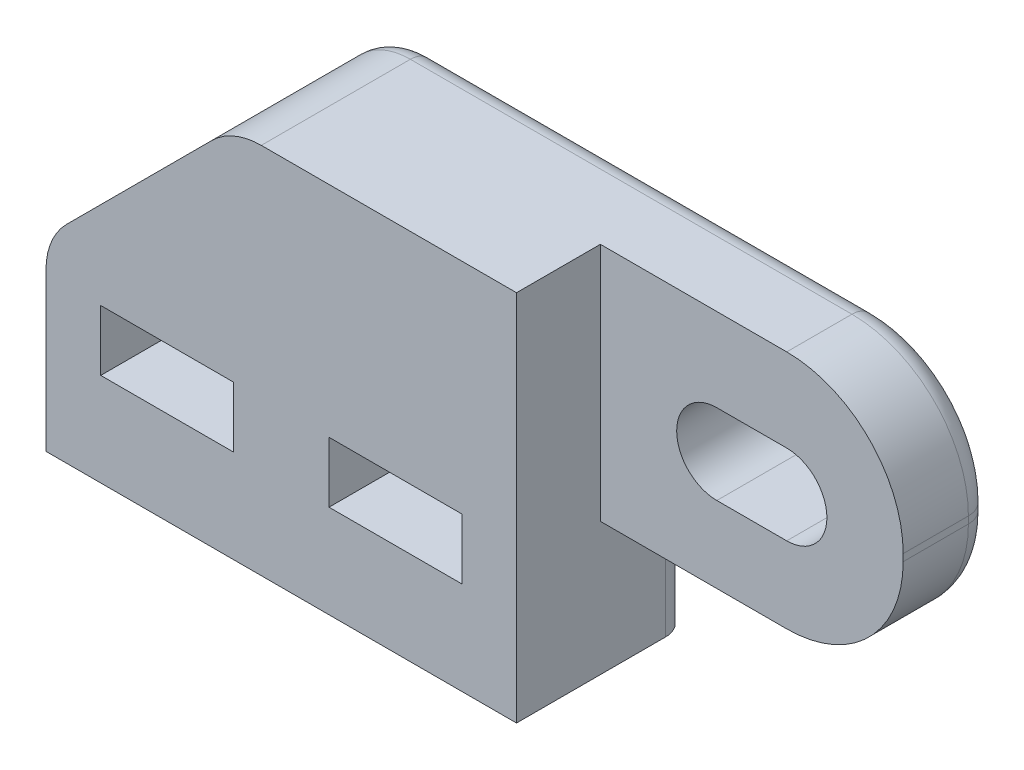
SolidWorks part; units mm, degrees
material "ABS"
ref_plane "Front Plane" through (0, 0, 0) normal (0, 0, 1) x (1, 0, 0)
ref_plane "Top Plane" through (0, 0, 0) normal (0, 1, 0) x (1, 0, 0)
ref_plane "Right Plane" through (0, 0, 0) normal (1, 0, 0) x (0, 0, -1)
sketch "Sketch1" plane through (0, 0, 0) normal (0, 0, 1) x (1, 0, 0)
  line L0 (0, 0) -> (20.2, 0)
  line L1 (20.2, 0) -> (20.2, 5.7)
  line L2 (20.2, 5.7) -> (33.2, 5.7)
  line L3 (33.2, 5.7) -> (33.2, 16)
  line L4 (33.2, 16) -> (0, 16)
  line L5 (0, 16) -> (0, 0)
  line L6 (25.2, 16) -> (25.2, 5.7) construction
  line L7 (25.2, 12.425) -> (28.2, 12.425)
  line L8 (25.2, 8.975) -> (28.2, 8.975)
  arc A0 (25.2, 12.425) -> (25.2, 8.975) centre (25.2, 10.7) ccw
  arc A1 (28.2, 8.975) -> (28.2, 12.425) centre (28.2, 10.7) ccw
  dimension "D6" = 3.45
  dimension "D1" = 20.2
  dimension "D2" = 5.7
  dimension "D3" = 5
  dimension "D4" = 5
  dimension "D5" = 16
  dimension "D7" = 8
  dimension "D8" = 3
extrude "Boss-Extrude1" add sketch "Sketch1" along normal blind 7.4
sketch "Sketch2" plane through (33.2, 0, 0) normal (1, 0, 0) x (0, 0, -1)
  line L1 (-3.8, 5.7) -> (-7.4, 5.7)
  line L2 (-3.8, 5.7) -> (-3.8, 16)
  line L3 (-3.8, 16) -> (-7.4, 16)
  line L4 (-7.4, 5.7) -> (-7.4, 16)
  line L5 (-7.4, 16) -> (0, 16) construction
  dimension "D1" = 3.6
extrude "Cut-Extrude1" cut sketch "Sketch2" against normal up to surface (13 mm away) up to face at (20.2, 2.85, 3.7)
sketch "Sketch4" plane through (0, 0, 0) normal (0, -1, 0) x (1, 0, 0)
  line L0 (10.1, 0) -> (10.1, 7.4) construction
  line L3 (20.2, 2.75) -> (0, 2.75) construction
  line L5 (0, 7.4) -> (20.2, 7.4) construction
  line L7 (0, 0) -> (20.2, 0) construction
  line L8 (0, 7.4) -> (0, 0) construction
  line L9 (20.2, 7.4) -> (20.2, 0) construction
  circle A0 centre (15, 2.75) radius 1.725
  circle A1 centre (5.2, 2.75) radius 1.725
  dimension "D1" = 3.45
  dimension "D2" = 9.8
  dimension "D3" = 10.1
  dimension "D4" = 2.75
extrude "Cut-Extrude3" cut sketch "Sketch4" against normal blind 9
sketch "Sketch3" plane through (0, 0, 0) normal (0, 0, -1) x (-1, 0, 0)
  line L0 (-15, 9) -> (-15, 0) construction
  line L1 (-17.85, 6.6) -> (-12.15, 6.6)
  line L2 (-17.85, 6.6) -> (-17.85, 4)
  line L3 (-17.85, 4) -> (-12.15, 4)
  line L4 (-12.15, 6.6) -> (-12.15, 4)
  line L5 (-17.85, 6.6) -> (-12.15, 4) construction
  line L6 (-17.85, 4) -> (-12.15, 6.6) construction
  line L7 (-8.05, 6.6) -> (-2.35, 6.6)
  line L8 (-8.05, 6.6) -> (-8.05, 4)
  line L9 (-8.05, 4) -> (-2.35, 4)
  line L10 (-2.35, 6.6) -> (-2.35, 4)
  line L11 (-8.05, 6.6) -> (-2.35, 4) construction
  line L12 (-8.05, 4) -> (-2.35, 6.6) construction
  line L13 (-5.2, 9) -> (-5.2, 0) construction
  point P0 (-15, 5.3)
  point P5 (-5.2, 5.3)
  dimension "D1" = 9.8
  dimension "D2" = 4
  dimension "D3" = 2.6
  dimension "D4" = 5.7
extrude "Cut-Extrude4" cut sketch "Sketch3" against normal through all
chamfer "Chamfer1" distance 8 angle 45 1 edges at (0, 16, 3.7)
fillet "Fillet4" radius 3 2 edges at (8, 16, 3.7) (0, 8, 3.7)
fillet "Fillet5" radius 5 2 edges at (33.2, 5.7, 1.9) (33.2, 16, 1.9)
fillet "Fillet6" radius 1 10 edges at (24.2, 5.7, 0) (31.7355, 7.1645, 0) (33.2, 10.85, 0) (31.7355, 14.5355, 0) (18.7213, 16, 0) (8.0946, 15.7716, 0) (4, 12, 0) (0.2284, 7.9054, 0) (0, 3.3787, 0) (20.2, 2.85, 0)
equation "\"D6@Sketch1\"=3.00mm+\"print_free@Parameters@Parameters.SLDPRT\""
equation "\"D1@Sketch4\"=3.00mm+\"print_free@Parameters@Parameters.SLDPRT\""
equation "\"D4@Sketch3\"= 5.50mm+\"print_fit@Parameters@Parameters.SLDPRT\""
equation "\"D3@Sketch3\"=2.40mm+\"print_fit@Parameters@Parameters.SLDPRT\""
equation "\"D8@Sketch1\"=\"LinkADist@Parameters@Parameters.SLDPRT\""
